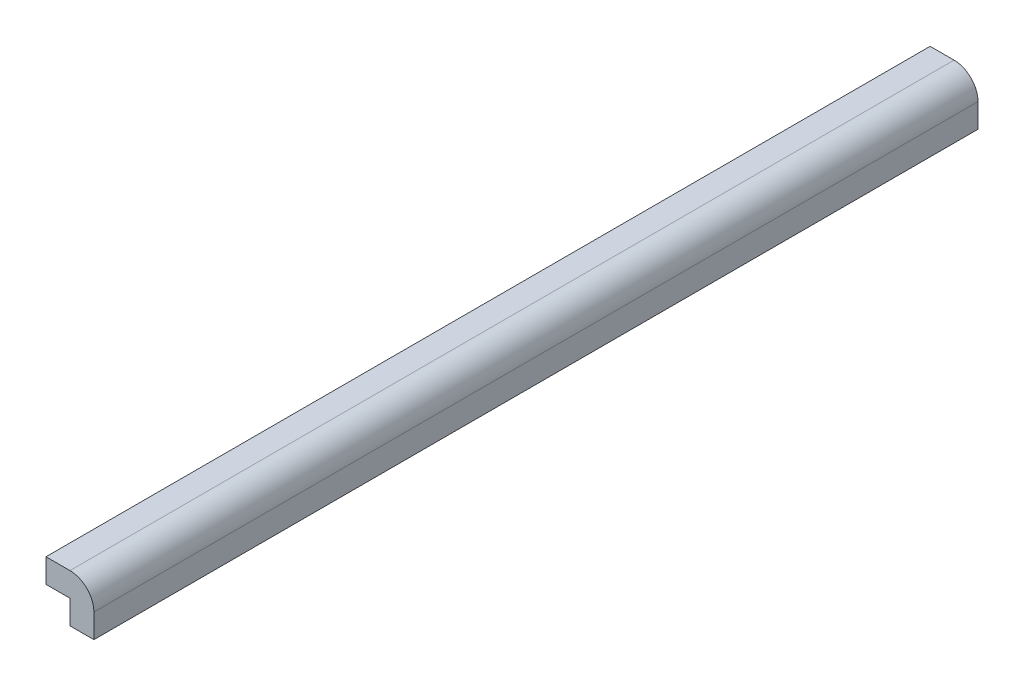
SolidWorks part; units mm, degrees
ref_plane "Front Plane" through (0, 0, 0) normal (0, 0, 1) x (1, 0, 0)
ref_plane "Top Plane" through (0, 0, 0) normal (0, 1, 0) x (1, 0, 0)
ref_plane "Right Plane" through (0, 0, 0) normal (1, 0, 0) x (0, 0, -1)
sketch "Sketch1" plane through (0, 0, 0) normal (0, 0, 1) x (1, 0, 0)
  line L1 (0, 0) -> (-13, 0)
  line L3 (0, 13) -> (-13, 13)
  line L4 (-13, 0) -> (-13, 13)
  line L6 (0, 0) -> (0, -13)
  line L7 (0, -13) -> (13, -13)
  line L8 (13, 0) -> (13, -13)
  arc A0 (0, 13) -> (13, 0) centre (0, 0) cw
  dimension "D5" = 13
  dimension "D1" = 13
  dimension "D2" = 13
  dimension "D3" = 13
  dimension "D4" = 13
extrude "Boss-Extrude1" add sketch "Sketch1" along normal blind 480
